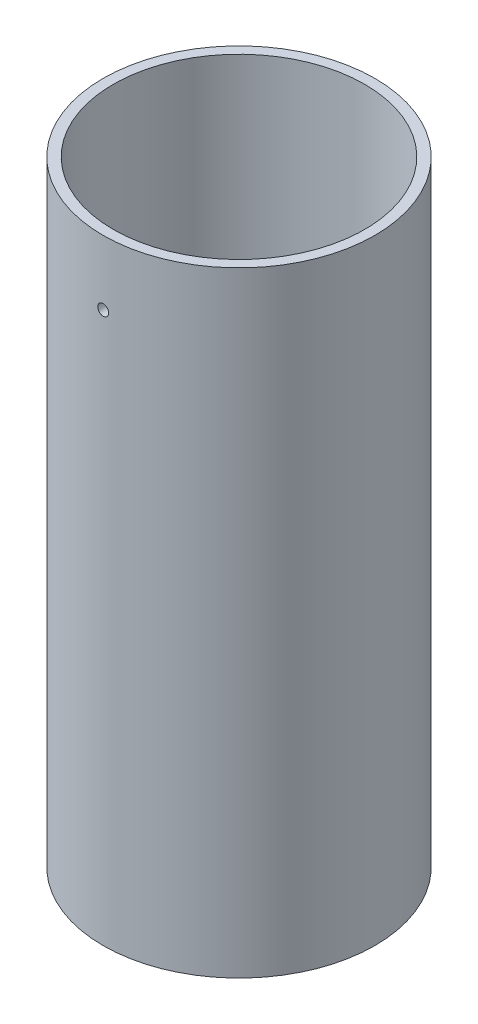
SolidWorks part; units mm, degrees
material "玻璃"
ref_plane "前视基准面" through (0, 0, 0) normal (0, 0, 1) x (1, 0, 0)
ref_plane "上视基准面" through (0, 0, 0) normal (0, 1, 0) x (1, 0, 0)
ref_plane "右视基准面" through (0, 0, 0) normal (1, 0, 0) x (0, 0, -1)
sketch "草图1" plane through (0, 0, 0) normal (0, 1, 0) x (1, 0, 0)
  circle A0 centre (0, 0) radius 40
  circle A1 centre (0, 0) radius 37
  dimension "D1" = 80
  dimension "D2" = 3
extrude "凸台-拉伸1" add sketch "草图1" along normal mid plane 181
hole_wizard "M3 间隙孔1" positions "3D草图1" profile "草图2" hole size "M3" standard "GB"
sketch3d "3D草图1"
  line L0 (0, 0, 0) -> (0, 0, 40) construction
  line L1 (0, 0, 40) -> (0, 71.5, 40) construction
  point P0 (0, 71.5, 40)
  dimension "D1" = 19
sketch "草图2" plane through (0, 71.5, 40) normal (1, 0, 0) x (0, -1, 0)
  line L0 (0, 0) -> (0, 3)
  line L1 (0, 3) -> (1.6, 3)
  line L2 (1.6, 3) -> (1.6, 0)
  line L5 (1.6, 0) -> (0, 0)
  line L11 (0, -6.35) -> (0, 107.95) construction
  dimension "通孔孔直径" = 3.2
  dimension "通孔孔深度" = 3
